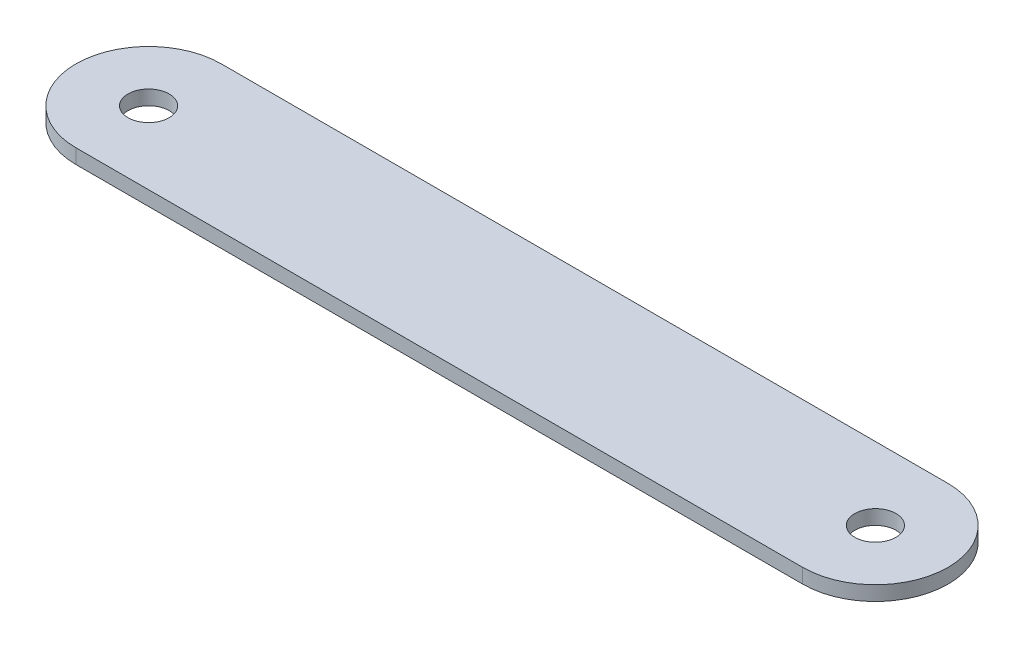
SolidWorks part; units mm, degrees
ref_plane "Plano frontal" through (0, 0, 0) normal (0, 0, 1) x (1, 0, 0)
ref_plane "Plano superior" through (0, 0, 0) normal (0, 1, 0) x (1, 0, 0)
ref_plane "Plano direito" through (0, 0, 0) normal (1, 0, 0) x (0, 0, -1)
sketch "Esboço3" plane through (0, 0, 0) normal (0, 1, 0) x (1, 0, 0)
  line L2 (-50, 15) -> (100, 15)
  line L3 (-50, -15) -> (100, -15)
  arc A0 (100, 15) -> (100, -15) centre (100, 0) cw
  arc A1 (-50, 15) -> (-50, -15) centre (-50, 0) ccw
  point P4 (0, 0)
  dimension "D2" = 30
  dimension "D4" = 15
  dimension "D1" = 150
  dimension "D5" = 50
extrude "Ressalto-extrusão2" add sketch "Esboço3" along normal blind 3
sketch "Esboço4" plane through (0, 3, 0) normal (0, 1, 0) x (1, 0, 0)
  line L0 (-65, 0) -> (115, 0) construction
  arc A0 (-50, 15) -> (-50, -15) centre (-50, 0) ccw construction
  arc A1 (100, -15) -> (100, 15) centre (100, 0) ccw construction
  circle A2 centre (-50, 0) radius 4.25
  circle A3 centre (100, 0) radius 4.25
  dimension "D1" = 8.5
  dimension "D2" = 8.5
extrude "Corte-extrusão1" cut sketch "Esboço4" against normal blind 10
